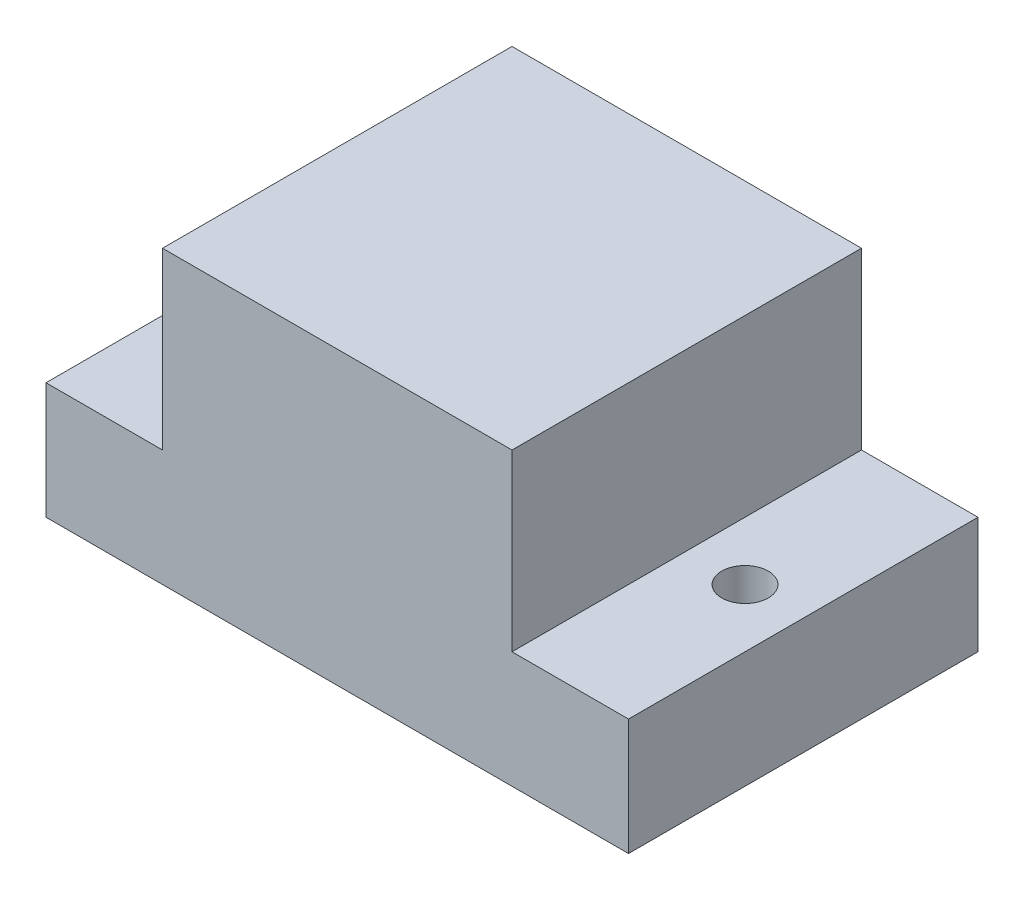
SolidWorks part; units mm, degrees
ref_plane "Alzado" through (0, 0, 0) normal (0, 0, 1) x (1, 0, 0)
ref_plane "Planta" through (0, 0, 0) normal (0, 1, 0) x (1, 0, 0)
ref_plane "Vista lateral" through (0, 0, 0) normal (1, 0, 0) x (0, 0, -1)
sketch "Croquis1" plane through (0, 0, 0) normal (0, 0, 1) x (1, 0, 0)
  line L0 (0, 31.3144) -> (0, -40.5928) construction
  line L1 (-15, -12.5) -> (15, -12.5)
  line L2 (-15, -12.5) -> (-15, 12.5)
  line L3 (-15, 12.5) -> (15, 12.5)
  line L4 (15, -12.5) -> (15, 12.5)
  line L5 (-15, -12.5) -> (15, 12.5) construction
  line L6 (-15, 12.5) -> (15, -12.5) construction
  line L7 (-15, -12.5) -> (-25, -12.5)
  line L8 (-15, -12.5) -> (-15, -2.5)
  line L9 (-15, -2.5) -> (-25, -2.5)
  line L10 (-25, -12.5) -> (-25, -2.5)
  line L11 (15, -2.5) -> (25, -2.5)
  line L12 (25, -12.5) -> (25, -2.5)
  line L13 (15, -12.5) -> (25, -12.5)
  line L14 (15, -12.5) -> (15, -2.5)
  point P0 (0, 0)
  dimension "D1" = 25
  dimension "D2" = 30
  dimension "D3" = 10
  dimension "D4" = 10
extrude "Saliente-Extruir1" add sketch "Croquis1" along normal mid plane 30 contours L10 L7 L2 L9 | L1 L4 L3 L2 | L4 L13 L12 L11
sketch "Croquis2" plane through (0, -2.5, 0) normal (0, 1, 0) x (1, 0, 0)
  line L0 (28.6336, 0) -> (-30.047, 0) construction
  line L1 (0, 16.8033) -> (0, -16.908) construction
  circle A0 centre (-20, 0) radius 2
  circle A1 centre (20, 0) radius 2
  dimension "D1" = 4
  dimension "D2" = 20
extrude "Cortar-Extruir1" cut sketch "Croquis2" against normal blind 30
